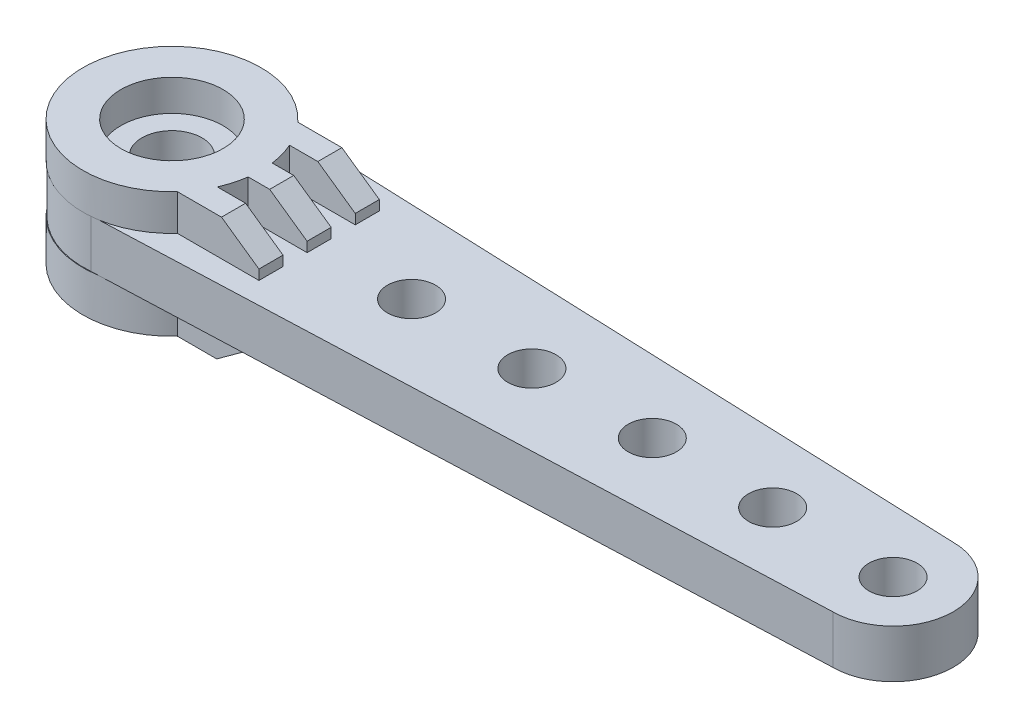
SolidWorks part; units mm, degrees
ref_plane "Front Plane" through (0, 0, 0) normal (0, 0, 1) x (1, 0, 0)
ref_plane "Top Plane" through (0, 0, 0) normal (0, 1, 0) x (1, 0, 0)
ref_plane "Right Plane" through (0, 0, 0) normal (1, 0, 0) x (0, 0, -1)
sketch "Sketch1" plane through (0, 0, 0) normal (0, 1, 0) x (1, 0, 0)
  line L1 (0.5657, 3.6312) -> (29.95, 2.5)
  line L2 (0.3073, -3.6621) -> (29.95, -2.5)
  arc A0 (0.5657, 3.6312) -> (0.3073, -3.6621) centre (0, 0) ccw
  arc A1 (29.95, -2.5) -> (29.95, 2.5) centre (29.95, 0) ccw
  circle A2 centre (29.95, 0) radius 1
  dimension "D1" = 7.35
  dimension "D3" = 5
  dimension "D5" = 2
  dimension "D4" = 29.6427
  dimension "D6" = 29.95
  dimension "D2" = 29.3843
extrude "Boss-Extrude1" add sketch "Sketch1" along normal blind 2
sketch "Sketch3" plane through (0, 0, 0) normal (0, -1, 0) x (1, 0, 0)
  circle A1 centre (0, 0) radius 3.7
  dimension "D1" = 7.4
extrude "Boss-Extrude2" add sketch "Sketch3" along normal blind 1.7
sketch "Sketch4" plane through (0, 2, 0) normal (0, 1, 0) x (1, 0, 0)
  circle A0 centre (0, 0) radius 3.7
  dimension "D1" = 7.4
extrude "Boss-Extrude3" add sketch "Sketch4" along normal blind 1.5
sketch "Sketch5" plane through (0, 3.5, 0) normal (0, 1, 0) x (1, 0, 0)
  circle A0 centre (0, 0) radius 1.25
  dimension "D1" = 2.5
extrude "Cut-Extrude2" cut sketch "Sketch5" against normal through all
sketch "Sketch6" plane through (0, -1.7, 0) normal (0, -1, 0) x (1, 0, 0)
  circle A0 centre (0, 0) radius 2.25
  dimension "D1" = 4.5
extrude "Cut-Extrude3" cut sketch "Sketch6" against normal blind 2.6
sketch "Sketch7" plane through (0, 3.5, 0) normal (0, 1, 0) x (1, 0, 0)
  circle A0 centre (0, 0) radius 2.125
  dimension "D1" = 4.25
extrude "Cut-Extrude4" cut sketch "Sketch7" against normal blind 1.3
sketch "Croquis3" plane through (0, 2, 0) normal (0, 1, 0) x (1, 0, 0)
  circle A0 centre (29.95, 0) radius 1
  circle A1 centre (24.95, 0) radius 1
  circle A2 centre (19.95, 0) radius 1
  circle A3 centre (14.95, 0) radius 1
  circle A4 centre (9.95, 0) radius 1
extrude "Cortar-Extruir1" cut sketch "Croquis3" against normal up to surface (2 mm away) up to face at (16.6933, 0, 0.0213)
sketch "Croquis5" plane through (0, 3.5, 0) normal (0, 1, 0) x (1, 0, 0)
  line L0 (3.7, 0) -> (6.7, 0) construction
  line L1 (6.7, -0.5) -> (6.7, 0.5)
  line L2 (6.7, 0.5) -> (3.6661, 0.5)
  line L3 (6.7, -0.5) -> (3.6661, -0.5)
  line L4 (3.1129, -2) -> (6.1129, -2) construction
  line L5 (6.1129, -2.5) -> (6.1129, -1.5)
  line L6 (6.1129, -1.5) -> (3.3823, -1.5)
  line L7 (6.1129, -2.5) -> (2.7276, -2.5)
  line L8 (6.1129, 2.5) -> (6.1129, 1.5)
  line L9 (6.1129, 2.5) -> (2.7276, 2.5)
  line L10 (6.1129, 1.5) -> (3.3823, 1.5)
  line L11 (3.1129, 2) -> (6.1129, 2) construction
  circle A0 centre (0, 0) radius 3.7 construction
  arc A1 (2.7276, -2.5) -> (3.3823, -1.5) centre (0, 0) ccw
  arc A2 (3.6661, -0.5) -> (3.6661, 0.5) centre (0, 0) ccw
  arc A3 (3.3823, 1.5) -> (2.7276, 2.5) centre (0, 0) ccw
  point P9 (6.7, 0)
  point P17 (6.1129, -2)
  dimension "D1" = 1
  dimension "D2" = 1
  dimension "D3" = 3
  dimension "D4" = 3
  dimension "D5" = 2
extrude "Saliente-Extruir3" add sketch "Croquis5" against normal up to surface (1.5 mm away) up to face at (24.95, 2, 1)
sketch "Croquis7" plane through (0, 0, 0.5) normal (0, 0, 1) x (1, 0, 0)
  line L0 (6.7, 2) -> (4.5578, 3.5)
  line L1 (2.7276, 3.5) -> (6.1129, 3.5) construction
  line L2 (4.5578, 3.5) -> (6.7, 3.5)
  line L3 (6.7, 3.5) -> (6.7, 2)
  dimension "D1" = 55
extrude "Cortar-Extruir2" cut sketch "Croquis7" against normal mid plane 10
sketch "Croquis8" plane through (0, 0, 0.5) normal (0, 0, 1) x (1, 0, 0)
  line L0 (6.1129, 2.4111) -> (6.1129, 2)
  line L1 (6.7, 2) -> (3.6661, 2) construction
  line L2 (6.1129, 2) -> (6.1129, 2.4111) construction
  line L3 (6.1129, 2) -> (6.7, 2)
  line L4 (6.7, 2) -> (6.1129, 2.4111)
extrude "Cortar-Extruir3" cut sketch "Croquis8" against normal mid plane 10
sketch "Croquis10" plane through (0, -1.7, 0) normal (0, -1, 0) x (1, 0, 0)
  line L0 (3.7, 0) -> (6.7, 0) construction
  line L1 (6.7, -0.5) -> (6.7, 0.5)
  line L2 (6.7, 0.5) -> (3.6661, 0.5)
  line L3 (6.7, -0.5) -> (3.6661, -0.5)
  line L4 (3.1129, -2) -> (6.1129, -2) construction
  line L5 (6.1129, -2.5) -> (6.1129, -1.5)
  line L6 (6.1129, -1.5) -> (3.3823, -1.5)
  line L7 (6.1129, -2.5) -> (2.7276, -2.5)
  line L8 (6.1129, 2.5) -> (6.1129, 1.5)
  line L9 (6.1129, 2.5) -> (2.7276, 2.5)
  line L10 (6.1129, 1.5) -> (3.3823, 1.5)
  line L11 (3.1129, 2) -> (6.1129, 2) construction
  arc A0 (2.7276, -2.5) -> (3.3823, -1.5) centre (0, 0) ccw
  arc A1 (3.6661, -0.5) -> (3.6661, 0.5) centre (0, 0) ccw
  arc A2 (3.3823, 1.5) -> (2.7276, 2.5) centre (0, 0) ccw
  point P6 (6.7, 0)
  point P13 (6.1129, -2)
  point P21 (0, 0)
  circle M10 centre (0, 0) radius 3.7
  dimension "D1" = 1
  dimension "D2" = 1
  dimension "D3" = 3
  dimension "D4" = 3
  dimension "D5" = 2
extrude "Saliente-Extruir4" add sketch "Croquis10" against normal up to surface (1.7 mm away) contours L3 L1 L2 M10 | L7 L5 L6 M10 | L9 A2 L10 L8 up to face at (24.95, 0, 1)
sketch "Croquis11" plane through (0, 0, 0.5) normal (0, 0, 1) x (1, 0, 0)
  line L0 (6.7, 0) -> (4.3602, -1.7)
  line L1 (6.1129, -1.7) -> (2.7276, -1.7) construction
  line L2 (4.3602, -1.7) -> (6.7, -1.7)
  line L3 (6.7, -1.7) -> (6.7, 0)
  dimension "D1" = 54
extrude "Cortar-Extruir4" cut sketch "Croquis11" against normal mid plane 100
sketch "Croquis12" plane through (0, 0, 0.5) normal (0, 0, 1) x (1, 0, 0)
  line L0 (6.1129, 0) -> (6.1129, -0.4266)
  line L1 (6.1129, -0.4266) -> (6.7, 0)
  line L2 (6.7, 0) -> (6.1129, 0)
extrude "Cortar-Extruir5" cut sketch "Croquis12" against normal mid plane 100
